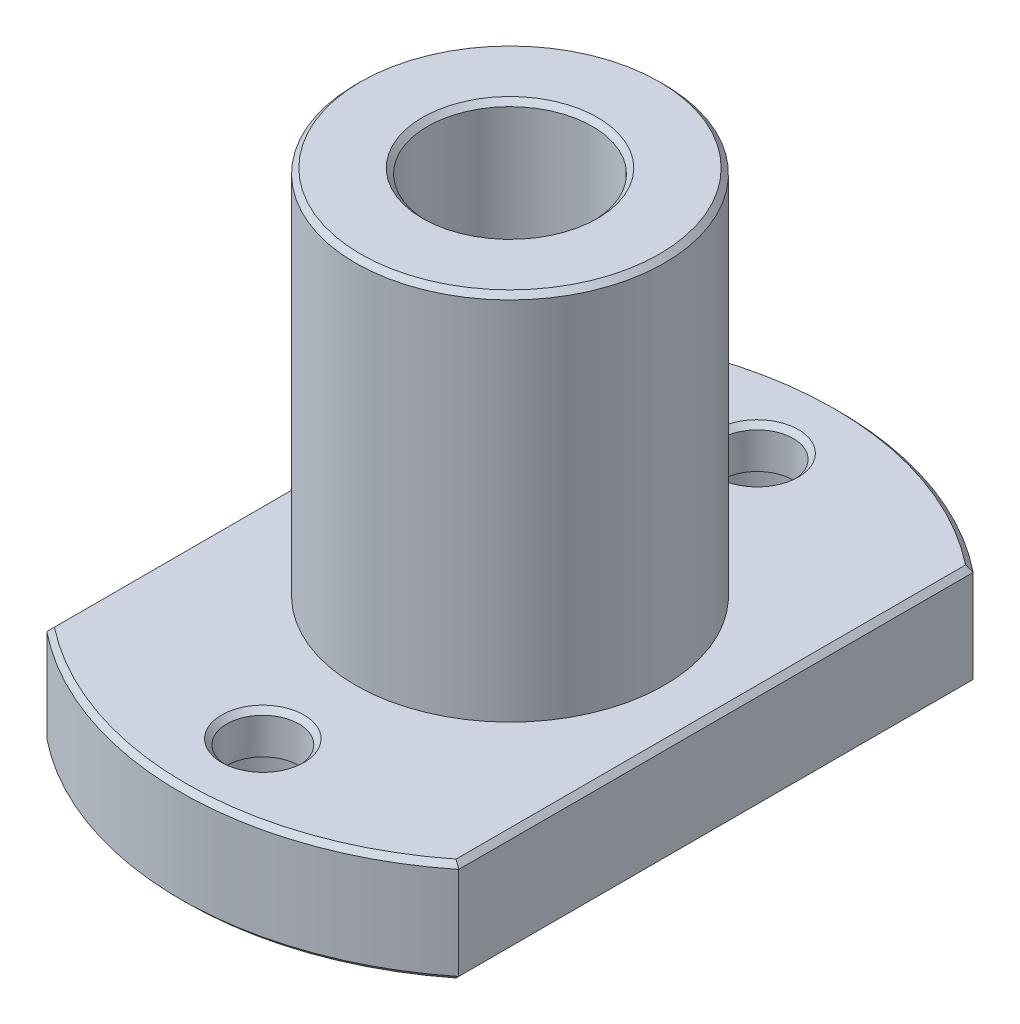
SolidWorks part; units mm, degrees
material "AISI 1010 Steel, hot rolled bar"
ref_plane "Front Plane" through (0, 0, 0) normal (0, 0, 1) x (1, 0, 0)
ref_plane "Top Plane" through (0, 0, 0) normal (0, 1, 0) x (1, 0, 0)
ref_plane "Right Plane" through (0, 0, 0) normal (1, 0, 0) x (0, 0, -1)
sketch "Sketch1" plane through (0, 0, 0) normal (0, 1, 0) x (1, 0, 0)
  line L0 (0, 16) -> (0, -16) construction
  circle A0 centre (0, 0) radius 16
  dimension "D1" = 32
extrude "Boss-Extrude1" add sketch "Sketch1" along normal blind 5
sketch "Sketch2" plane through (0, 0, 0) normal (0, 1, 0) x (1, 0, 0)
  line L0 (0, 16) -> (0, -16) construction
  line L1 (-10, 12.49) -> (-10, -12.49)
  line L2 (10, 12.49) -> (10, -12.49)
  line L3 (-10, 16) -> (-10, -16) construction
  line L4 (10, 16) -> (10, -16) construction
  circle A0 centre (0, 0) radius 16 construction
  arc A1 (-10, 12.49) -> (-10, -12.49) centre (0, 0) ccw
  arc A2 (10, -12.49) -> (10, 12.49) centre (0, 0) ccw
  dimension "D3" = 32
  dimension "D1" = 10
  dimension "D2" = 10
extrude "Cut-Extrude1" cut sketch "Sketch2" along normal blind 5
sketch "Sketch3" plane through (0, 5, 0) normal (0, 1, 0) x (1, 0, 0)
  circle A0 centre (0, 0) radius 7.5
  dimension "D1" = 15
extrude "Boss-Extrude2" add sketch "Sketch3" along normal blind 18
sketch "Sketch4" plane through (0, 23, 0) normal (0, 1, 0) x (1, 0, 0)
  circle A0 centre (0, 0) radius 4
  dimension "D1" = 8
extrude "Cut-Extrude2" cut sketch "Sketch4" against normal blind 23
sketch "Sketch5" plane through (0, 5, 0) normal (0, 1, 0) x (1, 0, 0)
  circle A0 centre (0, 0) radius 12 construction
  circle A1 centre (0, 12) radius 1.75
  circle A2 centre (0, -12) radius 1.75
  dimension "D1" = 24
  dimension "D2" = 3.5
  dimension "D3" = 3.5
extrude "Cut-Extrude3" cut sketch "Sketch5" against normal blind 5
sketch "Sketch6" plane through (0, 0, 0) normal (0, -1, 0) x (1, 0, 0)
  circle A0 centre (0, 12) radius 3
  circle A1 centre (0, -12) radius 3
  dimension "D1" = 6
  dimension "D2" = 6
extrude "Cut-Extrude4" cut sketch "Sketch6" against normal blind 3
chamfer "Chamfer1" distance 0.25 angle 45 15 edges at (0, 0, 9) (0, 0, 4) (0, 0, -15) (10, 0, 0) (0, 0, 16) (0, 0, -16) (-10, 0, 0) (0, 5, 16) (0, 5, -16) (10, 5, 0) (-10, 5, 0) (0, 23, 7.5) (0, 5, -10.25) (0, 5, 13.75) (0, 23, 4)
